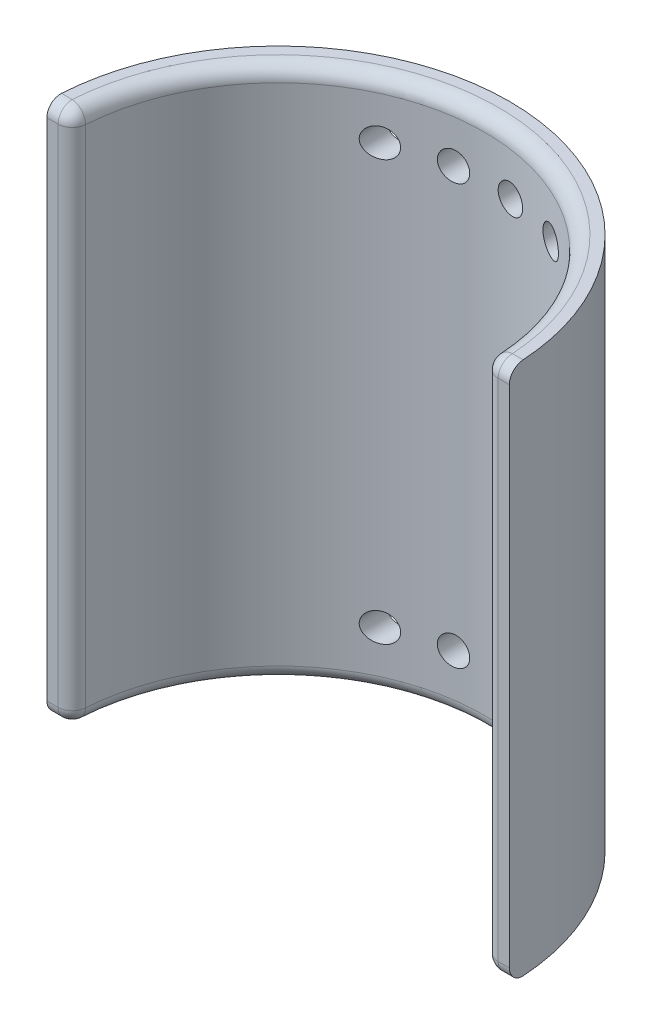
SolidWorks part; units mm, degrees
ref_plane "前基準面" through (0, 0, 0) normal (0, 0, 1) x (1, 0, 0)
ref_plane "上基準面" through (0, 0, 0) normal (0, 1, 0) x (1, 0, 0)
ref_plane "右基準面" through (0, 0, 0) normal (1, 0, 0) x (0, 0, -1)
sketch "草圖2" plane through (0, 0, 0) normal (0, 1, 0) x (1, 0, 0)
  circle A0 centre (0, 0) radius 32.5
  dimension "D1" = 65
extrude "填料-伸長1" add sketch "草圖2" along normal blind 75
sketch "草圖3" plane through (0, 75, 0) normal (0, 1, 0) x (1, 0, 0)
  circle A0 centre (0, 0) radius 29
  dimension "D1" = 58
extrude "除料-伸長1" cut sketch "草圖3" against normal mid plane 285
sketch "草圖4" plane through (0, 0, 0) normal (0, 0, 1) x (1, 0, 0)
  line L1 (-32.5, 75) -> (32.5, 75)
  line L2 (-32.5, 75) -> (-32.5, 0)
  line L3 (-32.5, 0) -> (32.5, 0)
  line L4 (32.5, 75) -> (32.5, 0)
extrude "除料-伸長2" cut sketch "草圖4" along normal blind 50
sketch "草圖5" plane through (0, 0, 0) normal (0, 0, 1) x (1, 0, 0)
  line L0 (29, 75) -> (-29, 75) construction
  line L1 (-29, 37.5) -> (40.0106, 37.5) construction
  line L2 (-29, 0) -> (-29, 75) construction
  circle A0 centre (-4, 67) radius 2
  circle A1 centre (4, 67) radius 2
  circle A2 centre (12, 67) radius 2
  circle A3 centre (-12, 67) radius 2
  circle A4 centre (-12, 8) radius 2
  circle A5 centre (12, 8) radius 2
  circle A6 centre (4, 8) radius 2
  circle A7 centre (-4, 8) radius 2
  dimension "D1" = 4
  dimension "D5" = 8
  dimension "D6" = 4
  dimension "D7" = 4
  dimension "D2" = 4
  dimension "D3" = 8
  dimension "D4" = 8
  dimension "D8" = 8
extrude "除料-伸長3" cut sketch "草圖5" against normal blind 50
fillet "圓角1" radius 2 2 edges at (29, 37.5, 0) (-29, 37.5, 0)
fillet "圓角2" radius 2 5 edges at (31.7177, 75, 0) (29.5676, 75, -0.5409) (-31.7177, 75, 0) (-29.5676, 75, -0.5409) (0, 75, -29)
fillet "圓角3" radius 2 5 edges at (31.7177, 0, 0) (29.5676, 0, -0.5409) (-31.7177, 0, 0) (-29.5676, 0, -0.5409) (0, 0, -29)
